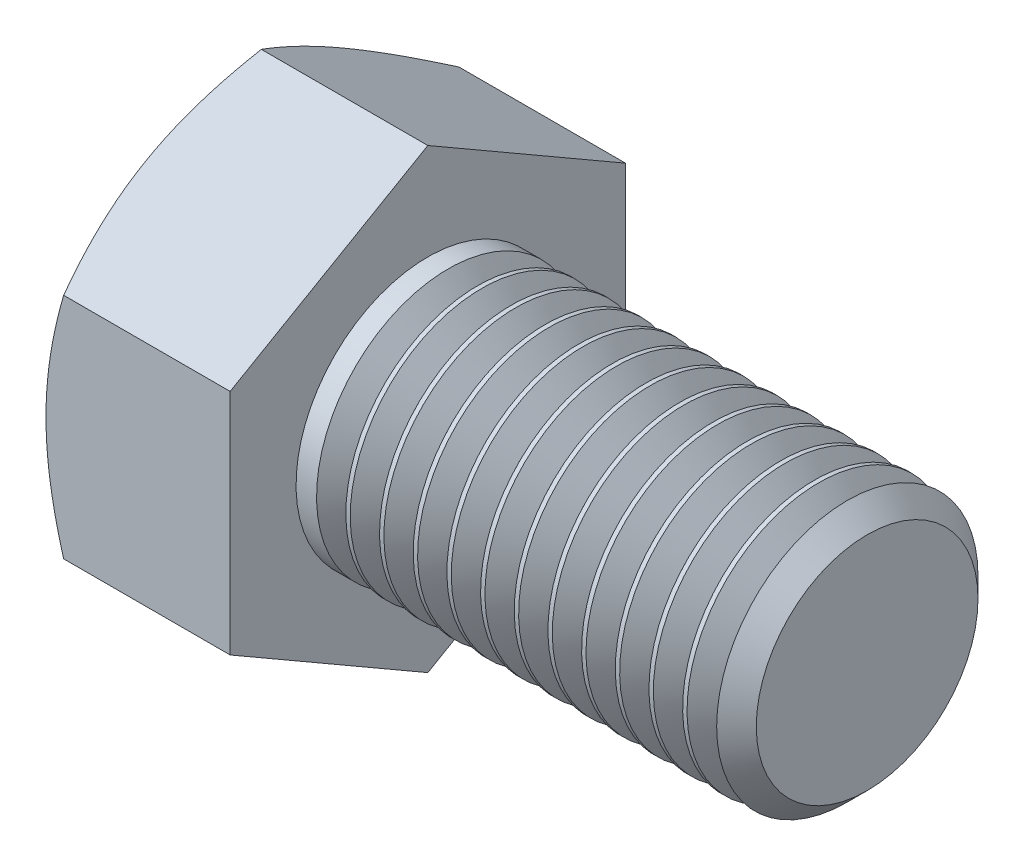
SolidWorks part; units mm, degrees
extrude "BaseHead" add sketch "Sketch1" along normal blind 13.3096
sketch "Sketch1" plane through (0, 0, 0) normal (1, 0, 0) x (0, 0, -1)
  line L0 (14.2875, 8.2489) -> (14.2875, -8.2489)
  line L1 (-14.2875, 8.2489) -> (-14.2875, -8.2489)
  line L2 (14.2875, -8.2489) -> (0, -16.4978)
  line L3 (0, -16.4978) -> (-14.2875, -8.2489)
  line L4 (14.2875, 8.2489) -> (0, 16.4978)
  line L5 (0, 16.4978) -> (-14.2875, 8.2489)
  dimension "Width_flats" = 28.575
  dimension "D2" = 120
  dimension "D3" = 14.2875
  dimension "D4" = 14.2875
  dimension "D5" = 14.2875
ref_plane "Plane1" through (0, 0, 0) normal (0, 0, 1) x (1, 0, 0)
ref_plane "Plane2" through (0, 0, 0) normal (0, 1, 0) x (1, 0, 0)
ref_plane "Plane3" through (0, 0, 0) normal (1, 0, 0) x (0, 0, -1)
sketch "BodySke" plane through (0, 0, 0) normal (0, 0, 1) x (1, 0, 0)
  line L0 (0, 8.2489) -> (0, -8.2489) construction
  line L1 (0, 0) -> (45.0596, 0)
  line L2 (0, 0) -> (0, 9.525)
  line L3 (0, 9.525) -> (43.547, 9.525)
  line L4 (45.0596, 0) -> (45.0596, 8.0124)
  line L5 (13.3096, 16.4978) -> (13.3096, 8.2489) construction
  line L6 (45.0596, 8.0124) -> (43.547, 9.525)
  line L7 (0, 0) -> (96.52, 0) construction
  line L8 (45.0596, -8.0124) -> (43.547, -9.525) construction
  line L9 (0, -9.525) -> (43.547, -9.525) construction
  line L10 (15.8496, 15.24) -> (15.8496, -2.54) construction
  line L11 (13.3096, 15.24) -> (13.3096, -2.54) construction
  line L12 (13.3096, 8.2489) -> (13.3096, -8.2489) construction
  dimension "Diameter" = 19.05
revolve "BaseBody" add sketch "BodySke" angle 360 about L7
cosmetic thread "ThreadCosmetic" [suppressed] parameters "Thread_length"=29.21, "Thread_minor"=16.0249
sketch "Sketch3" plane through (0, 0, 0) normal (0, 0, 1) x (1, 0, 0)
  line L0 (0, 14.2875) -> (4.9423, 22.8478)
  line L1 (0, 16.4978) -> (0, 8.2489) construction
  line L2 (4.9423, 22.8478) -> (4.9423, 29.1978)
  line L3 (4.9423, 29.1978) -> (-12.7, 29.1978)
  line L4 (-12.7, 29.1978) -> (-12.7, 14.2875)
  line L5 (-12.7, 14.2875) -> (0, 14.2875)
  line L6 (0, 0) -> (99.06, 0) construction
  line L7 (13.3096, 16.4978) -> (0, 16.4978) construction
  dimension "D1" = 14.2875
  dimension "D2" = 6.35
  dimension "D3" = 12.7
  dimension "D4" = 6.35
  dimension "Head_ch_ang" = 30
revolve "HeadChamfer" cut sketch "Sketch3" angle 360 about L6
fillet "HeadFillet" [suppressed] radius 1.524
sketch "ThdSchSke" plane through (0, 0, 0) normal (0, 0, 1) x (1, 0, 0)
  line L0 (15.8496, -8.0124) -> (14.7905, -9.525)
  line L1 (15.8496, -8.0124) -> (16.9087, -9.525)
  line L2 (16.9087, -9.525) -> (16.9087, -11.9063)
  line L3 (-3.175, 0) -> (5.1513, 0) construction
  line L5 (16.9087, -11.9063) -> (14.7905, -11.9063)
  line L6 (14.7905, -11.9063) -> (14.7905, -9.525)
  dimension "Thread_minor" = 16.0249
  dimension "Diameter" = 19.05
  dimension "Start" = 15.8496
revolve "ThreadSchematic" cut sketch "ThdSchSke" angle 360 about L3
pattern_linear "ThdSchPat" count 12 spacing 2.4342 along (1, 0, 0) of "ThreadSchematic"
equation "\"D3@Sketch1\" = \"Width_flats@Sketch1\" / 2"
equation "\"D4@Sketch1\" = \"D3@Sketch1\""
equation "\"D5@Sketch1\" = \"D4@Sketch1\""
equation "\"Thread_minor@ThreadCosmetic\" = \"Minor_dia@BodySke\""
equation "\"D1@Sketch3\" = \"Width_flats@Sketch1\" / 2"
equation "\"Thread_length@ThreadCosmetic\" = ((sgn( (\"Length@BodySke\" - \"Advance@BodySke\" ) - \"Thread_nom@BodySke\" )-1)*( (\"Length@BodySke\" - \"Advance@BodySke\" ) - \"Thread_nom@BodySke\" ))/-2+ \"Thread_nom@BodySke\""
equation "\"Thread_minor@ThdSchSke\" = \"Minor_dia@BodySke\""
equation "\"Diameter@ThdSchSke\" = \"Diameter@BodySke\""
equation "\"Overcut@ThdSchSke\" = \"Diameter@BodySke\" * 1.25"
equation "\"Start@ThdSchSke\" = \"Head_ht@BaseHead\" + \"Length@BodySke\" - \"Thread_length@ThreadCosmetic\"  '---Non-countersunk---"
equation "\"Num_threads@ThdSchPat\" = int( \"Thread_length@ThreadCosmetic\" / \"Advance@BodySke\" + 0.999 )  + 1"
equation "\"Advance@ThdSchPat\" = \"Thread_length@ThreadCosmetic\" /  (\"Num_threads@ThdSchPat\" - 1) 'relax it"
equation "\"Num_threads@ThdSchPat\" = \"Num_threads@ThdSchPat\" - sgn( \"Num_threads@ThdSchPat\" - 1) '---chamfered tips only---"
